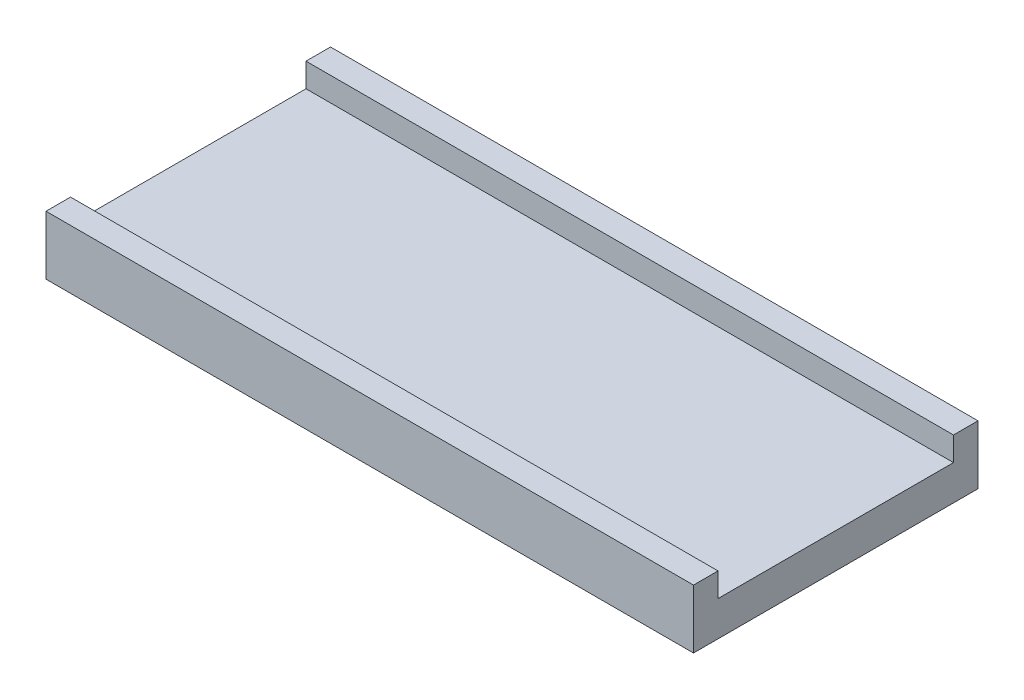
SolidWorks part; units mm, degrees
ref_plane "Front Plane" through (0, 0, 0) normal (0, 0, 1) x (1, 0, 0)
ref_plane "Top Plane" through (0, 0, 0) normal (0, 1, 0) x (1, 0, 0)
ref_plane "Right Plane" through (0, 0, 0) normal (1, 0, 0) x (0, 0, -1)
sketch "Sketch1" plane through (0, 0, 0) normal (0, 1, 0) x (1, 0, 0)
  line L1 (82.5, 36.25) -> (-82.5, 36.25)
  line L2 (82.5, 36.25) -> (82.5, -36.25)
  line L3 (82.5, -36.25) -> (-82.5, -36.25)
  line L4 (-82.5, 36.25) -> (-82.5, -36.25)
  line L5 (82.5, 36.25) -> (-82.5, -36.25) construction
  line L6 (82.5, -36.25) -> (-82.5, 36.25) construction
  point P0 (0, 0)
  point P11 (0, 0)
  dimension "D1" = 72.5
  dimension "D2" = 165
extrude "Boss-Extrude1" add sketch "Sketch1" along normal blind 15 contours L2 L1 L4 L3
sketch "Sketch2" plane through (0, 15, 0) normal (0, 1, 0) x (1, 0, 0)
  line L0 (-82.5, 36.25) -> (-82.5, -36.25) construction
  line L1 (82.5, -30) -> (-82.5, -30)
  line L2 (82.5, -30) -> (82.5, 30)
  line L3 (82.5, 30) -> (-82.5, 30)
  line L4 (-82.5, -30) -> (-82.5, 30)
  line L5 (82.5, -30) -> (-82.5, 30) construction
  line L6 (82.5, 30) -> (-82.5, -30) construction
  point P0 (0, 0)
  dimension "D1" = 60
extrude "Cut-Extrude1" cut sketch "Sketch2" against normal blind 6.1
